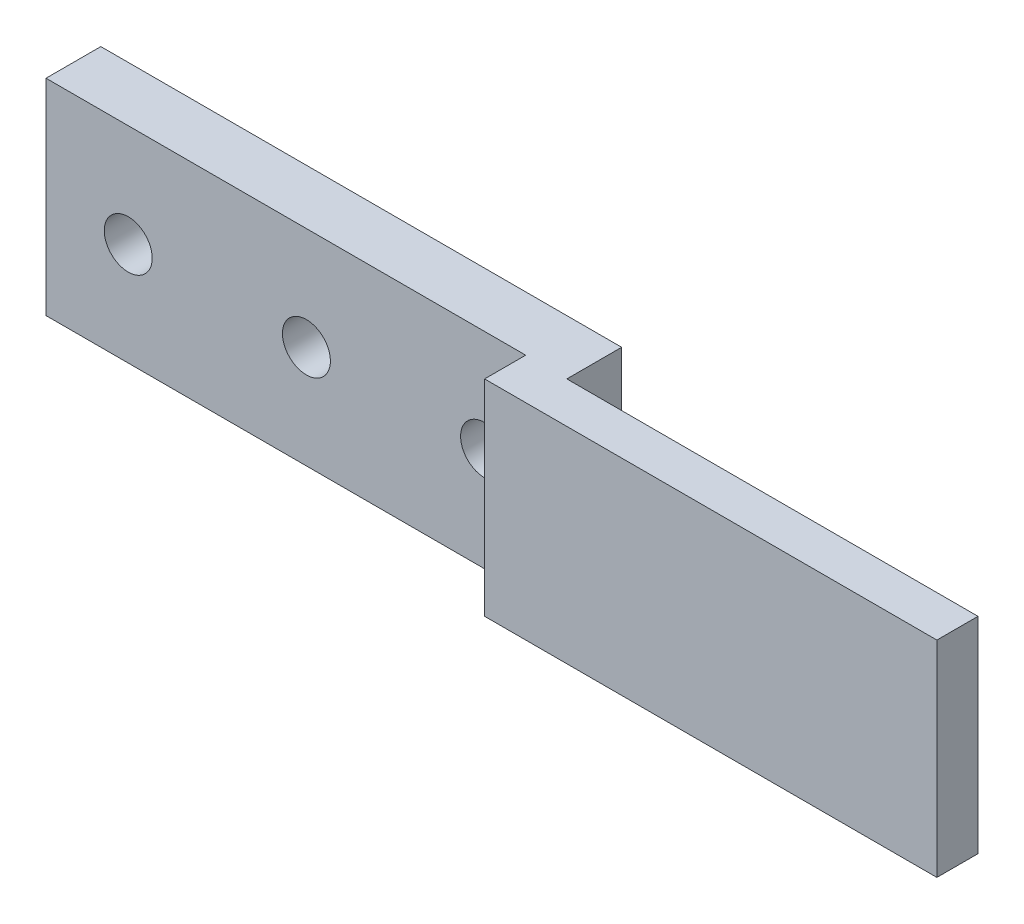
SolidWorks part; units mm, degrees
ref_plane "Plano frontal" through (0, 0, 0) normal (0, 0, 1) x (1, 0, 0)
ref_plane "Plano superior" through (0, 0, 0) normal (0, 1, 0) x (1, 0, 0)
ref_plane "Plano direito" through (0, 0, 0) normal (1, 0, 0) x (0, 0, -1)
sketch "Esboço1" plane through (0, 0, 0) normal (0, 0, 1) x (1, 0, 0)
  line L1 (12.5, -7.5) -> (-12.5, -7.5)
  line L2 (12.5, -7.5) -> (12.5, 7.5)
  line L3 (12.5, 7.5) -> (-12.5, 7.5)
  line L4 (-12.5, -7.5) -> (-12.5, 7.5)
  line L5 (12.5, -7.5) -> (-12.5, 7.5) construction
  line L6 (12.5, 7.5) -> (-12.5, -7.5) construction
  point P0 (0, 0)
  dimension "D1" = 25
extrude "Ressalto-extrusão1" add sketch "Esboço1" along normal blind 3
sketch "Esboço3" plane through (0, 0, 3) normal (0, 0, 1) x (1, 0, 0)
  line L5 (-12.5, -7.5) -> (12.5, -7.5) construction
  line L6 (12.5, 7.5) -> (9.5, 7.5)
  line L7 (12.5, 7.5) -> (12.5, -7.5)
  line L8 (12.5, -7.5) -> (9.5, -7.5)
  line L9 (9.5, 7.5) -> (9.5, -7.5)
  dimension "D1" = 3
extrude "Ressalto-extrusão2" add sketch "Esboço3" along normal blind 3
sketch "Esboço5" plane through (12.5, 0, 0) normal (1, 0, 0) x (0, 0, -1)
  line L5 (-6, 7.5) -> (0, 7.5) construction
  line L6 (-6, -7.5) -> (-3, -7.5)
  line L7 (-6, -7.5) -> (-6, 7.5)
  line L8 (-6, 7.5) -> (-3, 7.5)
  line L9 (-3, -7.5) -> (-3, 7.5)
extrude "Ressalto-extrusão3" add sketch "Esboço5" along normal blind 30
ref_plane "Plano1" through (-12.5, 7.5, 3) normal (-1, 0, 0) x (0, 0, 1)
sketch "Esboço8" plane through (0, 0, 0) normal (0, 0, -1) x (-1, 0, 0)
  line L1 (-12.5, 7.5) -> (12.5, 7.5)
  line L2 (-12.5, 7.5) -> (-12.5, -7.5)
  line L3 (-12.5, -7.5) -> (12.5, -7.5)
  line L4 (12.5, 7.5) -> (12.5, -7.5)
extrude "Ressalto-extrusão4" add sketch "Esboço8" along normal blind 1
sketch "Esboço9" plane through (0, 0, -1) normal (0, 0, -1) x (-1, 0, 0)
  line L0 (0, 7.5) -> (0, -7.5) construction
  line L1 (12.5, 7.5) -> (-12.5, 7.5) construction
  line L2 (-12.5, -7.5) -> (12.5, -7.5) construction
  line L3 (12.5, -7.5) -> (12.5, 7.5) construction
  line L4 (-12.5, 7.5) -> (-12.5, -7.5) construction
  circle A0 centre (-6.5, 0) radius 1.75
  circle A1 centre (6.5, 0) radius 1.75
  dimension "D1" = 6
  dimension "D2" = 6
  dimension "D3" = 3.5
  dimension "D4" = 13
extrude "Corte-extrusão1" cut sketch "Esboço9" against normal through all
sketch "Esboço10" plane through (-12.5, 0, 0) normal (-1, 0, 0) x (0, 0, 1)
  line L1 (-1, 7.5) -> (3, 7.5)
  line L2 (-1, 7.5) -> (-1, -7.5)
  line L3 (-1, -7.5) -> (3, -7.5)
  line L4 (3, 7.5) -> (3, -7.5)
extrude "Ressalto-extrusão5" add sketch "Esboço10" along normal blind 13
sketch "Esboço11" plane through (0, 0, 3) normal (0, 0, 1) x (1, 0, 0)
  circle A0 centre (-19.5, 0) radius 1.75
  circle A1 centre (-6.5, 0) radius 1.75 construction
  dimension "D1" = 13
extrude "Corte-extrusão2" cut sketch "Esboço11" against normal through all
